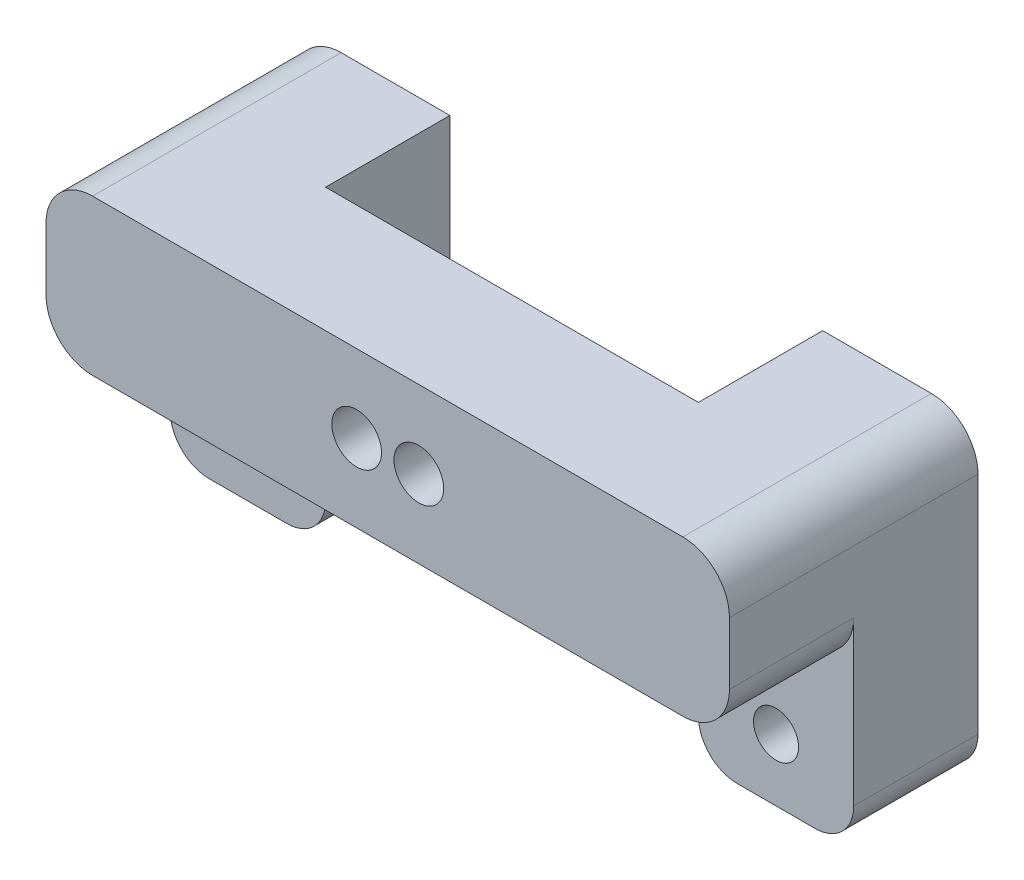
SolidWorks part; units mm, degrees
ref_plane "Front" through (0, 0, 0) normal (0, 0, 1) x (1, 0, 0)
ref_plane "Top" through (0, 0, 0) normal (0, 1, 0) x (1, 0, 0)
ref_plane "Right" through (0, 0, 0) normal (1, 0, 0) x (0, 0, -1)
sketch "Sketch1" plane through (0, 0, 0) normal (0, 0, 1) x (1, 0, 0)
  line L1 (0, 0) -> (44, 0)
  line L2 (0, 0) -> (0, -10)
  line L3 (0, -10) -> (44, -10)
  line L4 (44, 0) -> (44, -10)
  dimension "D1" = 10
  dimension "D2" = 44
extrude "Boss-Extrude1" add sketch "Sketch1" along normal blind 8
sketch "Sketch4" plane through (0, 0, 0) normal (0, 0, -1) x (-1, 0, 0)
  line L0 (-44, 0) -> (0, 0) construction
  line L1 (0, -10) -> (-10, -10)
  line L2 (0, -10) -> (0, 0)
  line L3 (0, 0) -> (-10, 0)
  line L4 (-10, -10) -> (-10, 0)
  line L6 (-44, -10) -> (-34, -10)
  line L7 (-44, -10) -> (-44, 0)
  line L8 (-44, 0) -> (-34, 0)
  line L9 (-34, -10) -> (-34, 0)
  dimension "D1" = 10
  dimension "D2" = 10
extrude "Boss-Extrude2" add sketch "Sketch4" along normal blind 8
sketch "Sketch3" plane through (0, 0, 8) normal (0, 0, 1) x (1, 0, 0)
  line L0 (0, -10) -> (44, -10) construction
  line L1 (0, 0) -> (0, -10) construction
  line L2 (44, -10) -> (44, 0) construction
  circle A0 centre (20, -5) radius 1.6
  circle A1 centre (24, -5) radius 1.6
  dimension "D1" = 3.2
  dimension "D2" = 3.2
  dimension "D3" = 5
  dimension "D4" = 5
  dimension "D5" = 20
  dimension "D6" = 20
extrude "Cut-Extrude2" cut sketch "Sketch3" against normal through all
sketch "Sketch5" plane through (0, -10, 0) normal (0, -1, 0) x (-1, 0, 0)
  line L1 (-10, 0) -> (0, 0)
  line L2 (-10, 0) -> (-10, 8)
  line L3 (-10, 8) -> (0, 8)
  line L4 (0, 0) -> (0, 8)
  line L5 (-34, 0) -> (-44, 0)
  line L6 (-34, 0) -> (-34, 8)
  line L7 (-34, 8) -> (-44, 8)
  line L8 (-44, 0) -> (-44, 8)
extrude "Boss-Extrude3" add sketch "Sketch5" along normal blind 10
sketch "Sketch6" plane through (0, 0, 0) normal (0, 0, 1) x (1, 0, 0)
  line L0 (10, -20) -> (0, -20) construction
  line L1 (44, -20) -> (34, -20) construction
  line L2 (44, -20) -> (44, -10) construction
  line L3 (10, -20) -> (10, -10) construction
  circle A0 centre (5, -16) radius 1.45
  circle A1 centre (39, -16) radius 1.45
  dimension "D1" = 2.9
  dimension "D2" = 2.9
  dimension "D3" = 4
  dimension "D4" = 4
  dimension "D5" = 5
  dimension "D6" = 5
extrude "Cut-Extrude3" cut sketch "Sketch6" against normal through all
fillet "Fillet2" radius 2.5 4 edges at (44, -20, -4) (34, -20, -4) (10, -20, -4) (0, -20, -4)
fillet "Fillet1" radius 3 4 edges at (0, -10, 4) (44, -10, 4) (44, 0, 0) (0, 0, 0)
